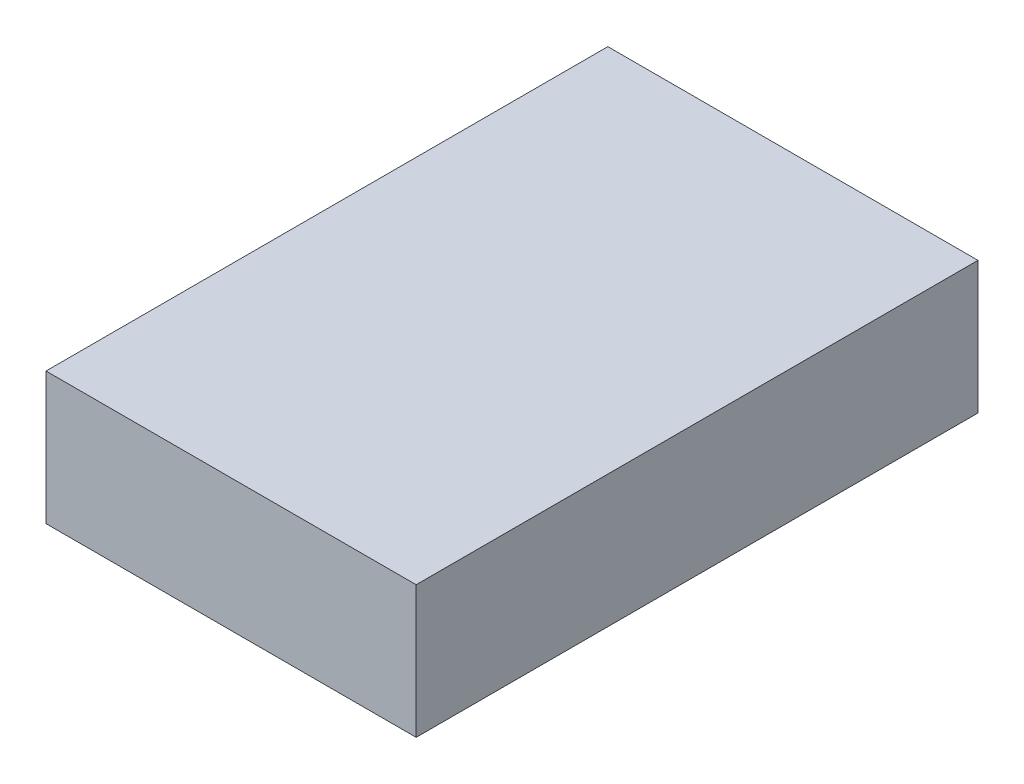
SolidWorks part; units mm, degrees
ref_plane "Front Plane" through (0, 0, 0) normal (0, 0, 1) x (1, 0, 0)
ref_plane "Top Plane" through (0, 0, 0) normal (0, 1, 0) x (1, 0, 0)
ref_plane "Right Plane" through (0, 0, 0) normal (1, 0, 0) x (0, 0, -1)
sketch "Sketch1" plane through (0, 0, 0) normal (0, 1, 0) x (1, 0, 0)
  line L1 (0, 0) -> (112, 0)
  line L2 (0, 0) -> (0, 170)
  line L3 (0, 170) -> (112, 170)
  line L4 (112, 0) -> (112, 170)
  dimension "D1" = 112
  dimension "D2" = 170
extrude "Boss-Extrude1" add sketch "Sketch1" along normal blind 40
